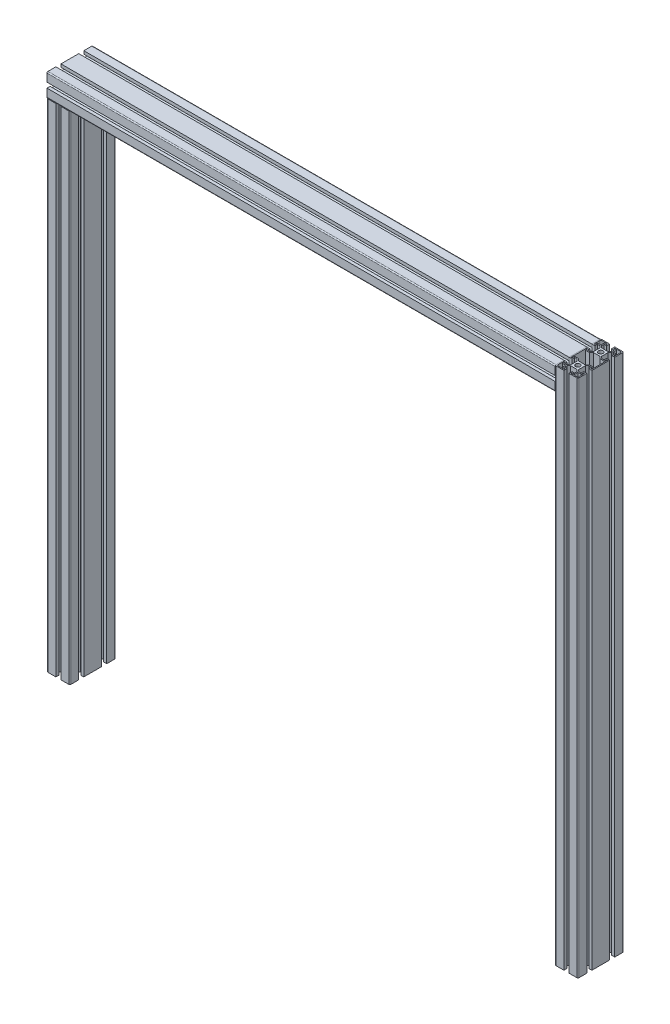
SolidWorks part; units mm, degrees
ref_plane "Front Plane" through (0, 0, 0) normal (0, 0, 1) x (1, 0, 0)
ref_plane "Top Plane" through (0, 0, 0) normal (0, 1, 0) x (1, 0, 0)
ref_plane "Right Plane" through (0, 0, 0) normal (1, 0, 0) x (0, 0, -1)
sketch3d "3DSketch2"
  line L0 (0, 0, 0) -> (0, 1000, 0)
  line L1 (0, 1000, 0) -> (1000, 1000, 0)
  line L2 (1000, 1000, 0) -> (1000, 0, 0)
  dimension "D2" = 1000
  dimension "D1" = 1000
other "Perfil aluminio 45 X 90(1)"
ref_plane "Plane2" through (1000, 1000, 0) normal (0, -1, 0) x (1, 0, 0)
sketch "Sketch1" plane through (1000, 1000, 0) normal (0, -1, 0) x (1, 0, 0)
  line L1 (-20.5, -29.5) -> (-20.5, -41)
  line L2 (-16.5, -27.5) -> (-22.5, -27.5)
  line L3 (12, -41) -> (12, -34.5)
  line L4 (7, -41) -> (12, -41)
  line L5 (7, -41) -> (7, -43)
  line L6 (18.5, -29.5) -> (20.5, -29.5)
  line L7 (22.5, 0) -> (-22.5, 0) construction
  line L8 (0, -45) -> (0, 45) construction
  line L9 (-8, -22.5) -> (8, -22.5) construction
  line L10 (22.5, -45) -> (0, -22.5) construction
  line L11 (5, -39) -> (5, -45)
  line L12 (22.5, -27.5) -> (22.5, -43)
  line L13 (-6.5858, -30.5) -> (6.5858, -30.5)
  line L14 (6.5858, -30.5) -> (10, -33.9142)
  line L15 (5, -39) -> (10, -39)
  line L16 (10, -39) -> (10, -33.9142)
  line L17 (5, -45) -> (20.5, -45)
  line L18 (18.5, -29.5) -> (18.5, -34.5)
  line L19 (7, -43) -> (18.5, -43)
  line L20 (18.5, -34.5) -> (12, -34.5)
  line L21 (8, -15.9142) -> (8, -29.0858)
  line L22 (8, -29.0858) -> (11.4142, -32.5)
  line L23 (16.5, -32.5) -> (11.4142, -32.5)
  line L24 (16.5, -27.5) -> (16.5, -32.5)
  line L25 (16.5, -27.5) -> (22.5, -27.5)
  line L26 (-16.5, -27.5) -> (-16.5, -32.5)
  line L27 (20.5, -29.5) -> (20.5, -41)
  line L28 (-16.5, -32.5) -> (-11.4142, -32.5)
  line L29 (-8, -29.0858) -> (-11.4142, -32.5)
  line L30 (-8, -15.9142) -> (-8, -29.0858)
  line L31 (-18.5, -34.5) -> (-12, -34.5)
  line L32 (-7, -43) -> (-18.5, -43)
  line L33 (-18.5, -29.5) -> (-18.5, -34.5)
  line L34 (-5, -45) -> (-20.5, -45)
  line L35 (-10, -39) -> (-10, -33.9142)
  line L36 (-5, -39) -> (-10, -39)
  line L37 (-6.5858, -30.5) -> (-10, -33.9142)
  line L38 (-22.5, -27.5) -> (-22.5, -43)
  line L39 (-5, -39) -> (-5, -45)
  line L40 (-18.5, -29.5) -> (-20.5, -29.5)
  line L41 (-7, -41) -> (-7, -43)
  line L42 (-7, -41) -> (-12, -41)
  line L43 (-12, -41) -> (-12, -34.5)
  line L44 (20.5, -2) -> (20.5, 2)
  line L45 (12, -10.5) -> (10.5858, -10.5)
  line L46 (10, -11.0858) -> (10.5858, -10.5)
  line L47 (-18.5, -15.5) -> (-20.5, -15.5)
  line L48 (-10, -11.0858) -> (-10.5858, -10.5)
  line L49 (-22.5, -17.5) -> (-22.5, 17.5)
  line L50 (-6.5858, -14.5) -> (-10, -11.0858)
  line L51 (-12, -10.5) -> (-10.5858, -10.5)
  line L52 (-20.5, -2) -> (-20.5, 2)
  line L53 (-20.5, 15.5) -> (-20.5, 2)
  line L54 (-18.5, -15.5) -> (-18.5, -10.5)
  line L55 (-16.5, 17.5) -> (-22.5, 17.5)
  line L56 (-18.5, -10.5) -> (-12, -10.5)
  line L57 (-8, -15.9142) -> (-11.4142, -12.5)
  line L58 (-16.5, -12.5) -> (-11.4142, -12.5)
  line L59 (20.5, -15.5) -> (20.5, -2)
  line L60 (-16.5, -17.5) -> (-16.5, -12.5)
  line L61 (16.5, -17.5) -> (22.5, -17.5)
  line L62 (16.5, -17.5) -> (16.5, -12.5)
  line L63 (16.5, -12.5) -> (11.4142, -12.5)
  line L64 (8, -15.9142) -> (11.4142, -12.5)
  line L65 (18.5, -10.5) -> (12, -10.5)
  line L66 (18.5, 15.5) -> (20.5, 15.5)
  line L67 (18.5, -15.5) -> (18.5, -10.5)
  line L68 (-6.5858, 14.5) -> (6.5858, 14.5)
  line L69 (6.5858, 14.5) -> (10, 11.0858)
  line L70 (18.5, 15.5) -> (18.5, 10.5)
  line L71 (6.5858, -14.5) -> (10, -11.0858)
  line L72 (-6.5858, -14.5) -> (6.5858, -14.5)
  line L73 (22.5, -17.5) -> (22.5, 17.5)
  line L74 (18.5, 10.5) -> (12, 10.5)
  line L75 (18.5, -15.5) -> (20.5, -15.5)
  line L76 (8, 15.9142) -> (11.4142, 12.5)
  line L77 (16.5, 12.5) -> (11.4142, 12.5)
  line L78 (16.5, 17.5) -> (16.5, 12.5)
  line L79 (-16.5, -17.5) -> (-22.5, -17.5)
  line L80 (-20.5, -15.5) -> (-20.5, -2)
  line L81 (16.5, 17.5) -> (22.5, 17.5)
  line L82 (-16.5, 17.5) -> (-16.5, 12.5)
  line L83 (20.5, 15.5) -> (20.5, 2)
  line L84 (-16.5, 12.5) -> (-11.4142, 12.5)
  line L85 (-8, 15.9142) -> (-11.4142, 12.5)
  line L86 (-18.5, 10.5) -> (-12, 10.5)
  line L87 (-18.5, 15.5) -> (-18.5, 10.5)
  line L88 (-12, 10.5) -> (-10.5858, 10.5)
  line L89 (-6.5858, 14.5) -> (-10, 11.0858)
  line L90 (-10, 11.0858) -> (-10.5858, 10.5)
  line L91 (-18.5, 15.5) -> (-20.5, 15.5)
  line L92 (10, 11.0858) -> (10.5858, 10.5)
  line L93 (12, 10.5) -> (10.5858, 10.5)
  line L94 (-12, 41) -> (-12, 34.5)
  line L95 (-7, 41) -> (-12, 41)
  line L96 (-7, 41) -> (-7, 43)
  line L97 (-18.5, 29.5) -> (-20.5, 29.5)
  line L98 (-5, 39) -> (-5, 45)
  line L99 (-22.5, 27.5) -> (-22.5, 43)
  line L100 (-6.5858, 30.5) -> (-10, 33.9142)
  line L101 (-5, 39) -> (-10, 39)
  line L102 (-10, 39) -> (-10, 33.9142)
  line L103 (-5, 45) -> (-20.5, 45)
  line L104 (-18.5, 29.5) -> (-18.5, 34.5)
  line L105 (-7, 43) -> (-18.5, 43)
  line L106 (-18.5, 34.5) -> (-12, 34.5)
  line L107 (-8, 15.9142) -> (-8, 29.0858)
  line L108 (-8, 29.0858) -> (-11.4142, 32.5)
  line L109 (-16.5, 32.5) -> (-11.4142, 32.5)
  line L110 (20.5, 29.5) -> (20.5, 41)
  line L111 (-16.5, 27.5) -> (-16.5, 32.5)
  line L112 (16.5, 27.5) -> (22.5, 27.5)
  line L113 (16.5, 27.5) -> (16.5, 32.5)
  line L114 (16.5, 32.5) -> (11.4142, 32.5)
  line L115 (8, 29.0858) -> (11.4142, 32.5)
  line L116 (8, 15.9142) -> (8, 29.0858)
  line L117 (18.5, 34.5) -> (12, 34.5)
  line L118 (7, 43) -> (18.5, 43)
  line L119 (18.5, 29.5) -> (18.5, 34.5)
  line L120 (5, 45) -> (20.5, 45)
  line L121 (10, 39) -> (10, 33.9142)
  line L122 (5, 39) -> (10, 39)
  line L123 (6.5858, 30.5) -> (10, 33.9142)
  line L124 (-6.5858, 30.5) -> (6.5858, 30.5)
  line L125 (22.5, 27.5) -> (22.5, 43)
  line L126 (5, 39) -> (5, 45)
  line L127 (18.5, 29.5) -> (20.5, 29.5)
  line L128 (7, 41) -> (7, 43)
  line L129 (7, 41) -> (12, 41)
  line L130 (12, 41) -> (12, 34.5)
  line L131 (-16.5, 27.5) -> (-22.5, 27.5)
  line L132 (-20.5, 29.5) -> (-20.5, 41)
  circle A0 centre (0, -22.5) radius 4.5
  circle A1 centre (0, 22.5) radius 4.5
  arc A2 (18.5, -43) -> (20.5, -41) centre (18.5, -41) ccw
  arc A3 (22.5, -43) -> (20.5, -45) centre (20.5, -43) cw
  arc A4 (-22.5, -43) -> (-20.5, -45) centre (-20.5, -43) ccw
  arc A5 (-18.5, -43) -> (-20.5, -41) centre (-18.5, -41) cw
  arc A6 (-22.5, 43) -> (-20.5, 45) centre (-20.5, 43) cw
  arc A7 (-20.5, 41) -> (-18.5, 43) centre (-18.5, 41) cw
  arc A8 (20.5, 45) -> (22.5, 43) centre (20.5, 43) cw
  arc A9 (20.5, 41) -> (18.5, 43) centre (18.5, 41) ccw
  point P0 (-22.5, -45)
  point P5 (-22.5, -22.5)
  point P9 (0, 0)
  point P11 (0, -14.5)
  point P49 (0, -30.5)
  point P67 (-8, -22.5)
  point P77 (8, -22.5)
  point P79 (8, 22.5)
  point P81 (-8, 22.5)
  point P83 (0, 30.5)
  point P85 (0, 14.5)
  point P94 (22.5, 0)
  point P110 (-20.5, 0)
  point P112 (-22.5, 0)
  point P113 (20.5, 0)
  point P152 (20.5, -43)
  point P158 (-22.5, -45)
  point P161 (-20.5, -43)
  point P167 (-20.5, 43)
  point P170 (22.5, 45)
  point P173 (20.5, 43)
  point P175 (0, -45)
  point P176 (22.5, -45)
  point P177 (0, 45)
  point P178 (22.5, -22.5)
  point P179 (-22.5, 22.5)
  point P180 (22.5, 22.5)
  point P181 (-22.5, 45)
  point P182 (22.5, 45)
  dimension "D1" = 2
  dimension "D2" = 9
other "Trim/Extend1"
